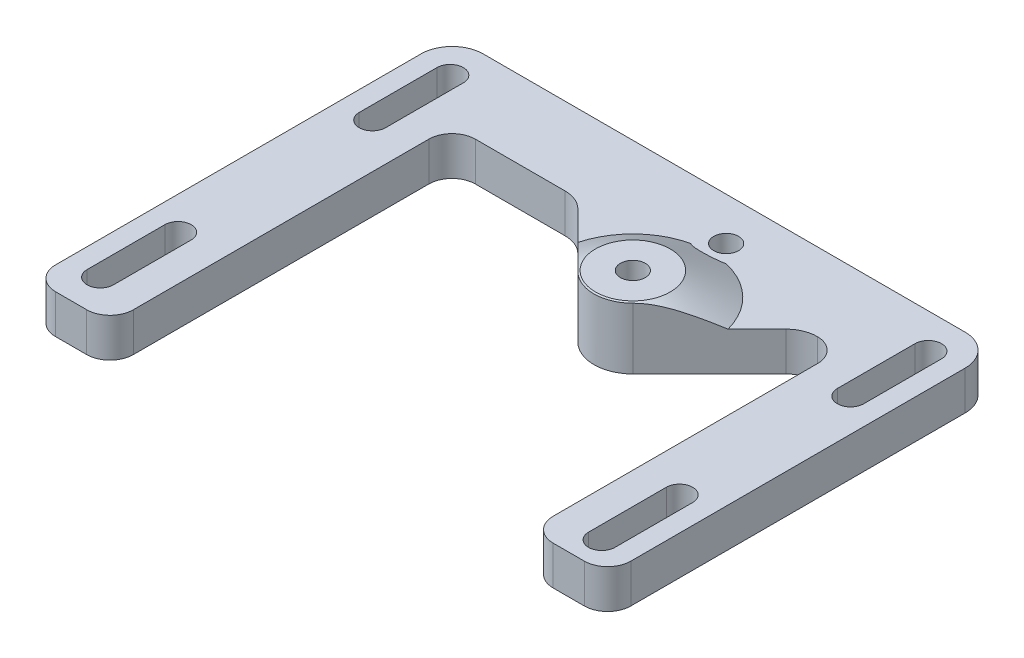
SolidWorks part; units mm, degrees
ref_plane "Front Plane" through (0, 0, 0) normal (0, 0, 1) x (1, 0, 0)
ref_plane "Top Plane" through (0, 0, 0) normal (0, 1, 0) x (1, 0, 0)
ref_plane "Right Plane" through (0, 0, 0) normal (1, 0, 0) x (0, 0, -1)
sketch "Sketch2" plane through (0, 0, 0) normal (0, 1, 0) x (1, 0, 0)
  line L0 (-25, 0) -> (-25, 37)
  line L1 (-35, 0) -> (-25, 0) construction
  line L2 (-35, 0) -> (-35, 46)
  line L3 (-31, 50) -> (31, 50)
  line L4 (35, 3) -> (35, 46)
  line L5 (-22, 40) -> (-10.4779, 40)
  line L6 (0, 56.6391) -> (0, -10.0045) construction
  line L7 (25, 3) -> (25, 37)
  line L8 (28, 0) -> (32, 0)
  line L9 (32.45, 45.5) -> (32.45, 35.5)
  line L10 (29.05, 45.5) -> (29.05, 35.5)
  line L11 (32.45, 13.5) -> (32.45, 3.5)
  line L12 (29.05, 13.5) -> (29.05, 3.5)
  line L13 (30.75, -5.4688) -> (30.75, 48.6617) construction
  line L14 (-30.75, -5.4688) -> (-30.75, 48.6617) construction
  line L15 (-29.05, 45.5) -> (-29.05, 35.5)
  line L16 (-32.45, 45.5) -> (-32.45, 35.5)
  line L17 (-29.05, 10.5) -> (-29.05, 0.5)
  line L18 (-32.45, 10.5) -> (-32.45, 0.5)
  line L19 (-35, 0) -> (-35, -1)
  line L20 (-32, -4) -> (-28, -4)
  line L21 (-25, -1) -> (-25, 0)
  line L22 (5.75, 68.2494) -> (5.75, 18.833) construction
  line L23 (23.75, 92.0099) -> (23.75, 52.7591) construction
  line L24 (-12.25, 92.0099) -> (-12.25, 52.7591) construction
  line L25 (74.1889, 52.5) -> (-54.4735, 52.5) construction
  line L26 (74.1889, 60.5) -> (-54.4735, 60.5) construction
  line L27 (2.2145, 28.9645) -> (-7.6495, 38.8284)
  line L28 (9.2855, 28.9645) -> (19.1495, 38.8284)
  line L29 (21.9779, 40) -> (22, 40)
  line L30 (-30.75, 72.4268) -> (-30.75, 54.1511) construction
  arc A0 (32.45, 45.5) -> (29.05, 45.5) centre (30.75, 45.5) ccw
  arc A1 (29.05, 35.5) -> (32.45, 35.5) centre (30.75, 35.5) ccw
  arc A2 (29.05, 3.5) -> (32.45, 3.5) centre (30.75, 3.5) ccw
  arc A3 (32.45, 13.5) -> (29.05, 13.5) centre (30.75, 13.5) ccw
  arc A4 (-32.45, 45.5) -> (-29.05, 45.5) centre (-30.75, 45.5) cw
  arc A5 (-29.05, 35.5) -> (-32.45, 35.5) centre (-30.75, 35.5) cw
  arc A6 (-32.45, 10.5) -> (-29.05, 10.5) centre (-30.75, 10.5) cw
  arc A7 (-29.05, 0.5) -> (-32.45, 0.5) centre (-30.75, 0.5) cw
  arc A8 (-35, 46) -> (-31, 50) centre (-31, 46) cw
  arc A9 (31, 50) -> (35, 46) centre (31, 46) cw
  circle A10 centre (5.75, 32.5) radius 1.6
  arc A11 (2.2145, 28.9645) -> (9.2855, 28.9645) centre (5.75, 32.5) ccw
  arc A12 (-28, -4) -> (-25, -1) centre (-28, -1) ccw
  arc A13 (-35, -1) -> (-32, -4) centre (-32, -1) ccw
  arc A14 (32, 0) -> (35, 3) centre (32, 3) ccw
  arc A15 (25, 3) -> (28, 0) centre (28, 3) ccw
  arc A16 (25, 37) -> (22, 40) centre (22, 37) ccw
  arc A17 (-25, 37) -> (-22, 40) centre (-22, 37) cw
  arc A18 (-7.6495, 38.8284) -> (-10.4779, 40) centre (-10.4779, 36) ccw
  arc A19 (19.1495, 38.8284) -> (21.9779, 40) centre (21.9779, 36) cw
  point P13 (0, 40)
  point P71 (20.3211, 40)
  point P81 (35, 0)
  point P87 (25, 0)
  point P90 (25, 40)
  point P93 (-25, 40)
  dimension "D6" = 3.4
  dimension "D8" = 10
  dimension "D9" = 3.4
  dimension "D12" = 3.4
  dimension "D13" = 1.7
  dimension "D14" = 1.7
  dimension "D15" = 10
  dimension "D16" = 35
  dimension "D23" = 4
  dimension "D24" = 3.2
  dimension "D25" = 3
  dimension "D3" = 3
  dimension "D26" = 3
  dimension "D27" = 3
  dimension "D28" = 13
  dimension "D29" = 3
  dimension "D30" = 10
  dimension "D31" = 4
  dimension "D32" = 4
  dimension "D33" = 45
  dimension "D34" = 45
  dimension "D22" = 4
  dimension "D1" = 35
  dimension "D2" = 25
  dimension "D4" = 40
  dimension "D5" = 30.75
  dimension "D7" = 4.5
  dimension "D10" = 32
  dimension "D11" = 10
  dimension "D17" = 4.5
  dimension "D18" = 5.75
  dimension "D19" = 18
  dimension "D20" = 7
  dimension "D21" = 15
extrude "Boss-Extrude1" add sketch "Sketch2" along normal blind 5
sketch "Sketch3" plane through (0, 5, 0) normal (0, 1, 0) x (1, 0, 0)
  circle A2 centre (5.75, 32.5) radius 10
extrude "Boss-Extrude2" add sketch "Sketch3" along normal blind 3 draft 60 contours A2
sketch "Sketch4" plane through (0, 0, 0) normal (0, -1, 0) x (1, 0, 0)
  line L0 (-3.9093, -35.0882) -> (2.2145, -28.9645)
  line L1 (9.2855, -28.9645) -> (15.4093, -35.0882)
  line L2 (31, -50) -> (-31, -50) construction
  circle A0 centre (5.75, -32.5) radius 1.6
  arc A1 (9.2855, -28.9645) -> (2.2145, -28.9645) centre (5.75, -32.5) ccw
  arc A2 (15.4093, -35.0882) -> (-3.9093, -35.0882) centre (5.75, -32.5) ccw
  circle A3 centre (5.75, -44.5) radius 1.6
  dimension "D1" = 3.2
  dimension "D2" = 3.2
  dimension "D3" = 5.5
extrude "Cut-Extrude1" cut sketch "Sketch4" against normal up to next
sketch "Sketch5" plane through (0, 0, 0) normal (0, -1, 0) x (1, 0, 0)
  circle A0 centre (5.75, -32.5) radius 3.5
extrude "Cut-Extrude2" cut sketch "Sketch5" against normal blind 3
sketch "Sketch6" plane through (0, 5, 0) normal (0, 1, 0) x (1, 0, 0)
  circle A0 centre (5.75, 44.5) radius 3.2
extrude "Cut-Extrude3" cut sketch "Sketch6" along normal blind 3
